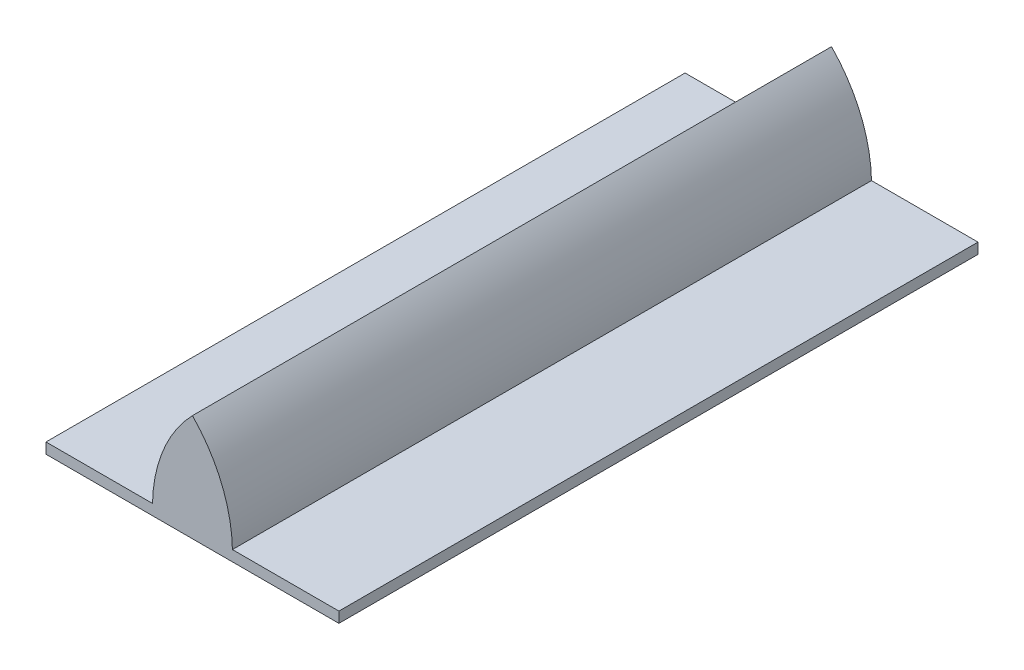
SolidWorks part; units mm, degrees
ref_plane "Front Plane" through (0, 0, 0) normal (0, 0, 1) x (1, 0, 0)
ref_plane "Top Plane" through (0, 0, 0) normal (0, 1, 0) x (1, 0, 0)
ref_plane "Right Plane" through (0, 0, 0) normal (1, 0, 0) x (0, 0, -1)
sketch "Sketch2" plane through (0, 0, 0) normal (0, 0, 1) x (1, 0, 0)
  line L0 (-121.2553, 165.7027) -> (-121.2553, -98.5044) construction
  line L1 (-295.8821, -9.6294) -> (-168.8821, -9.6294)
  line L2 (-295.8821, -9.6294) -> (-295.8821, 3.0706)
  line L3 (-295.8821, 3.0706) -> (-168.8821, 3.0706)
  line L5 (-168.8821, -9.6294) -> (-73.6285, -9.6294)
  line L6 (53.3715, 3.0706) -> (-73.6285, 3.0706)
  line L7 (53.3715, -9.6294) -> (53.3715, 3.0706)
  line L8 (53.3715, -9.6294) -> (-73.6285, -9.6294)
  arc A0 (-168.8821, 3.0706) -> (-121.2553, 117.5914) centre (0, 0) cw
  arc A1 (-73.6285, 3.0706) -> (-121.2553, 117.5914) centre (-242.5106, 0) ccw
  point P13 (-121.2553, -9.6294)
  dimension "D2" = 127
  dimension "D3" = 127
  dimension "D4" = 12.7
extrude "Boss-Extrude1" add sketch "Sketch2" along normal blind 762
